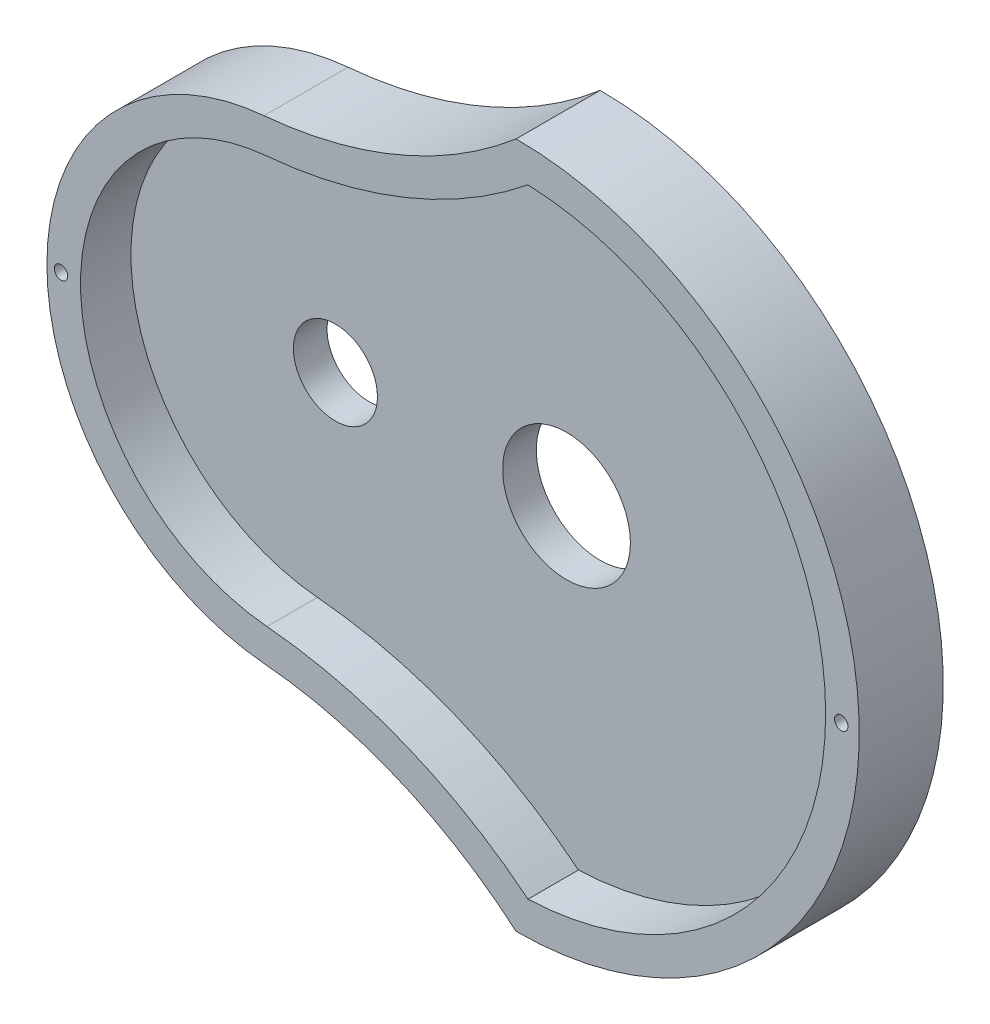
SolidWorks part; units mm, degrees
ref_plane "Front Plane" through (0, 0, 0) normal (0, 0, 1) x (1, 0, 0)
ref_plane "Top Plane" through (0, 0, 0) normal (0, 1, 0) x (1, 0, 0)
ref_plane "Right Plane" through (0, 0, 0) normal (1, 0, 0) x (0, 0, -1)
sketch "Sketch1" plane through (0, 0, 0) normal (0, 0, 1) x (1, 0, 0)
  arc A0 (0, -25.9296) -> (0, 25.9296) centre (0, 0) ccw
  arc A1 (-19.05, 17.9219) -> (-19.05, -17.9219) centre (-17.4625, 0) ccw
  arc A2 (-19.05, 17.9219) -> (0, 25.9296) centre (-22.0424, 51.7042) ccw
  arc A3 (-19.05, -17.9219) -> (0, -25.9296) centre (-22.0424, -51.7042) cw
  dimension "D1" = 35.9842
  dimension "D2" = 51.8592
  dimension "D3" = 17.4625
  dimension "D4" = 19.05
  dimension "D5" = 19.05
extrude "Boss-Extrude1" add sketch "Sketch1" along normal blind 6.35
shell "Shell1" thickness 2.54
sketch "Sketch2" plane through (0, 0, 6.35) normal (0, 0, 1) x (1, 0, 0)
  circle A0 centre (-34.3927, 0) radius 0.508
  circle A1 centre (24.5691, 0) radius 0.508
  dimension "D1" = 1.016
sketch "Sketch3" plane through (0, 0, 2.54) normal (0, 0, 1) x (1, 0, 0)
  circle A0 centre (0, 0) radius 4.826
  circle A1 centre (-17.4625, 0) radius 3.175
  dimension "D2" = 9.652
  dimension "D3" = 6.35
  dimension "D1" = 17.4625
extrude "Cut-Extrude1" cut sketch "Sketch3" against normal up to surface (2.54 mm away) up to face at (-6.8314, 0, 0)
extrude "Cut-Extrude2" cut sketch "Sketch2" against normal blind 1.27
equation "\"Input Gear OD\"= 0.4167in"
equation "\"Output Gear OD\"= 1.0417in"
equation "\"Input Gear Housing OD\"= \"Input Gear OD\" + 1"
equation "\"Output Gear Housing OD\"= \"Output Gear OD\" + 1"
equation "\"Inside Journal Bearong OD\"= 0.25in"
equation "\"Outside Journal Bearing OD\"= 0.38in"
equation "\"Gear Distance\"= 11 / 16"
equation "\"Thickness of Gear\"= 1 / 8"
equation "\"Pin Length\"=0.05"
equation "\"Thickness of Part\"= 0.0075"
equation "\"D1@Sketch1\"=\"Input Gear Housing OD\""
equation "\"D2@Sketch1\"=\"Output Gear Housing OD\""
equation "\"D3@Sketch1\"=\"Gear Distance\""
equation "\"D1@Boss-Extrude1\"=\"Thickness of Gear\" * 2"
equation "\"D1@Sketch3\"=\"Gear Distance\""
equation "\"D2@Sketch3\"=\"Outside Journal Bearing OD\""
equation "\"D3@Sketch3\"=\"Inside Journal Bearong OD\""
equation "\"D1@Cut-Extrude2\"=\"Pin Length\""
